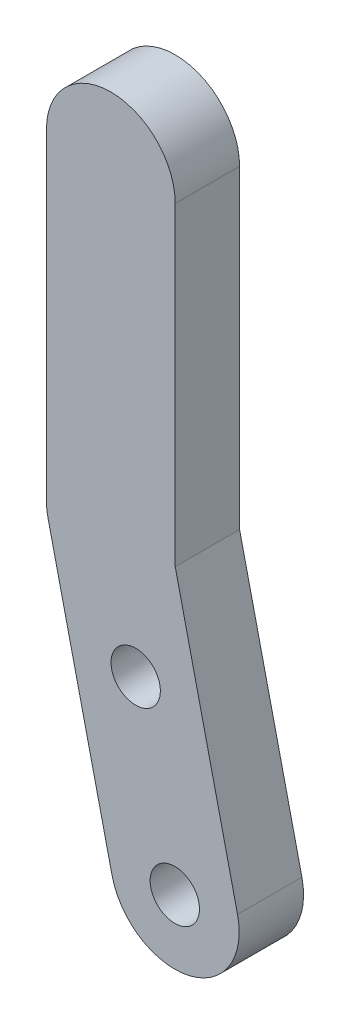
SolidWorks part; units mm, degrees
ref_plane "前基準面" through (0, 0, 0) normal (0, 0, 1) x (1, 0, 0)
ref_plane "上基準面" through (0, 0, 0) normal (0, 1, 0) x (1, 0, 0)
ref_plane "右基準面" through (0, 0, 0) normal (1, 0, 0) x (0, 0, -1)
sketch "Sketch1" plane through (0, 0, 0) normal (0, 0, 1) x (1, 0, 0)
  line L0 (0, 0) -> (-2.9806, 12.9104) construction
  line L1 (-2.9806, 12.9104) -> (-2.9806, 27.9104) construction
  line L2 (0, 0) -> (19.4615, 0) construction
  line L3 (0, 0) -> (-2.9806, 12.9104) construction
  line L4 (-2.9231, -0.6749) -> (-5.9037, 12.2356) construction
  line L5 (2.9231, 0.6749) -> (-0.0575, 13.5853) construction
  line L6 (-2.9806, 12.9104) -> (-2.9806, 27.9104) construction
  line L7 (-5.9806, 12.9104) -> (-5.9806, 27.9104) construction
  line L8 (0.0194, 12.9104) -> (0.0194, 27.9104) construction
  line L9 (-2.9231, -0.6749) -> (-5.9037, 12.2356)
  line L10 (2.9231, 0.6749) -> (0.0194, 13.2522)
  line L11 (0.0194, 13.2522) -> (0.0194, 27.9104)
  line L12 (-5.9806, 27.9104) -> (-5.9806, 12.9104)
  circle A0 centre (0, 0) radius 1.15
  circle A1 centre (-1.8221, 7.8924) radius 1.15
  arc A3 (-2.9231, -0.6749) -> (2.9231, 0.6749) centre (0, 0) ccw construction
  arc A4 (-0.0575, 13.5853) -> (-5.9037, 12.2356) centre (-2.9806, 12.9104) ccw construction
  arc A5 (-5.9806, 12.9104) -> (0.0194, 12.9104) centre (-2.9806, 12.9104) ccw construction
  arc A6 (0.0194, 27.9104) -> (-5.9806, 27.9104) centre (-2.9806, 27.9104) ccw construction
  arc A7 (-2.9231, -0.6749) -> (2.9231, 0.6749) centre (0, 0) ccw
  arc A8 (-5.9806, 27.9104) -> (0.0194, 27.9104) centre (-2.9806, 27.9104) cw
  arc A9 (-5.9806, 12.9104) -> (-5.9037, 12.2356) centre (-2.9806, 12.9104) ccw
  point P8 (-1.4903, 6.4552)
  point P13 (-2.9806, 20.4104)
  dimension "D4" = 2.3
  dimension "D5" = 8.1
  dimension "D6" = 6
  dimension "D7" = 6
  dimension "D8" = 3
  dimension "D1" = 13.25
  dimension "D2" = 167
  dimension "D3" = 15
extrude "Boss-Extrude1" add sketch "Sketch1" along normal blind 3
